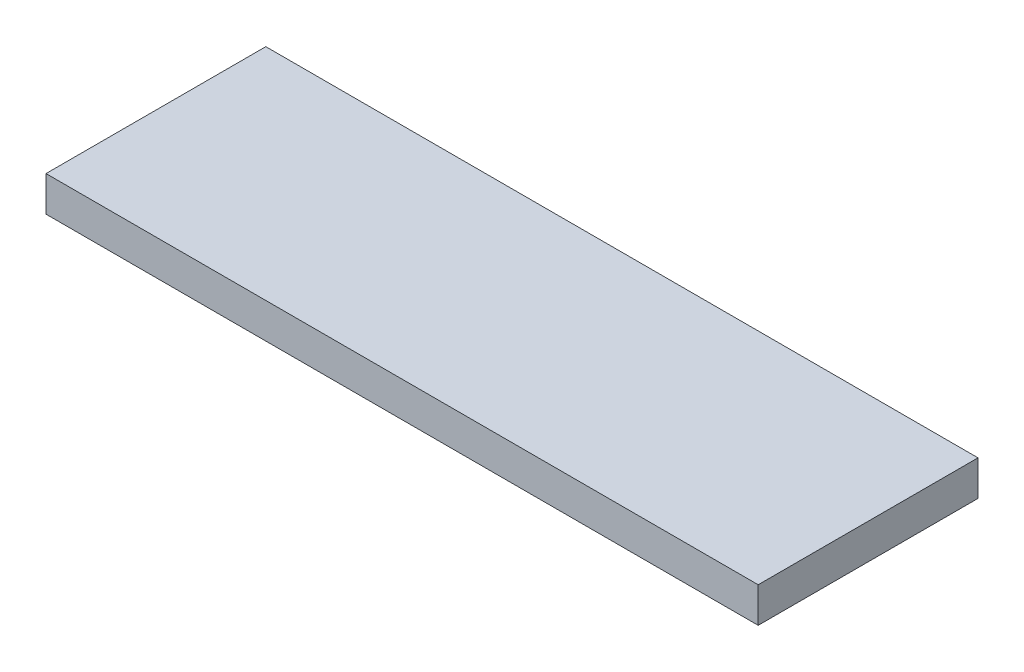
SolidWorks part; units mm, degrees
ref_plane "前视基准面" through (0, 0, 0) normal (0, 0, 1) x (1, 0, 0)
ref_plane "上视基准面" through (0, 0, 0) normal (0, 1, 0) x (1, 0, 0)
ref_plane "右视基准面" through (0, 0, 0) normal (1, 0, 0) x (0, 0, -1)
other "Configuration Table"
sketch "草图1" plane through (0, 0, 0) normal (0, 0, 1) x (1, 0, 0)
  line L0 (0, 0) -> (81, 0)
  line L1 (81, 0) -> (81, 4)
  line L2 (81, 4) -> (0, 4)
  line L3 (0, 4) -> (0, 0)
  dimension "width" = 81
  dimension "height" = 4
extrude "BlockExtrude" add sketch "草图1" along normal blind 25
